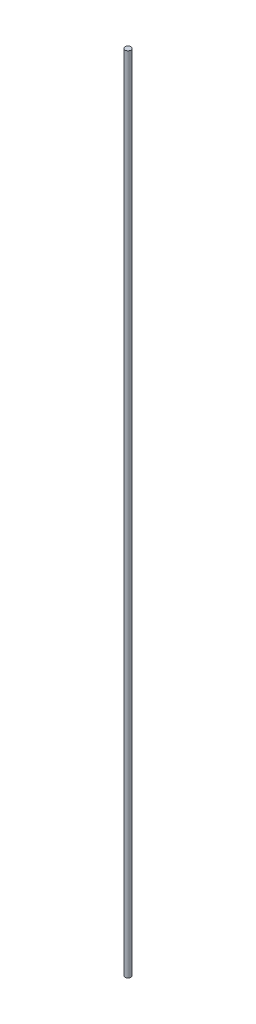
SolidWorks part; units mm, degrees
ref_plane "Front Plane" through (0, 0, 0) normal (0, 0, 1) x (1, 0, 0)
ref_plane "Top Plane" through (0, 0, 0) normal (0, 1, 0) x (1, 0, 0)
ref_plane "Right Plane" through (0, 0, 0) normal (1, 0, 0) x (0, 0, -1)
sketch "Sketch1" plane through (0, 0, 0) normal (0, 1, 0) x (1, 0, 0)
  circle A0 centre (0, 0) radius 1.13
  dimension "D1" = 2.26
extrude "Boss-Extrude1" add sketch "Sketch1" along normal blind 304.8
